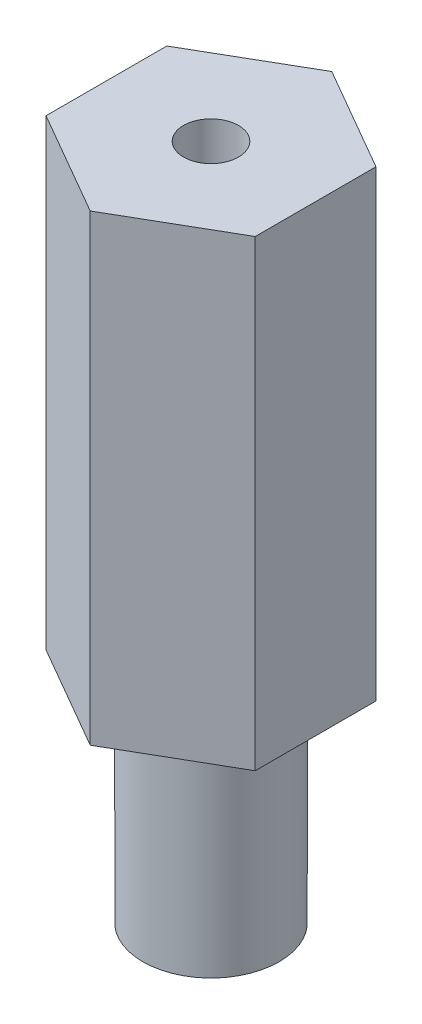
SolidWorks part; units mm, degrees
material "6061-T6 (SS)"
ref_plane "Front Plane" through (0, 0, 0) normal (0, 0, 1) x (1, 0, 0)
ref_plane "Top Plane" through (0, 0, 0) normal (0, 1, 0) x (1, 0, 0)
ref_plane "Right Plane" through (0, 0, 0) normal (1, 0, 0) x (0, 0, -1)
sketch "Sketch1" plane through (0, 0, 0) normal (0, 1, 0) x (1, 0, 0)
  line L1 (2.2606, 1.3052) -> (0, 2.6103)
  line L2 (0, 2.6103) -> (-2.2606, 1.3052)
  line L3 (-2.2606, 1.3052) -> (-2.2606, -1.3052)
  line L4 (-2.2606, -1.3052) -> (0, -2.6103)
  line L5 (0, -2.6103) -> (2.2606, -1.3052)
  line L6 (2.2606, -1.3052) -> (2.2606, 1.3052)
  circle A0 centre (0, 0) radius 2.2606 construction
  dimension "D1" = 4.5212
extrude "Boss-Extrude1" add sketch "Sketch1" along normal blind 10
sketch "Sketch2" plane through (0, 0, 0) normal (0, -1, 0) x (1, 0, 0)
  circle A0 centre (0, 0) radius 1.4732
  dimension "D1" = 2.9464
extrude "Boss-Extrude2" add sketch "Sketch2" along normal blind 4.6228
sketch "Sketch3" plane through (0, 10, 0) normal (0, 1, 0) x (1, 0, 0)
  circle A0 centre (0, 0) radius 0.5937
extrude "Cut-Extrude1" cut sketch "Sketch3" against normal blind 2.54
